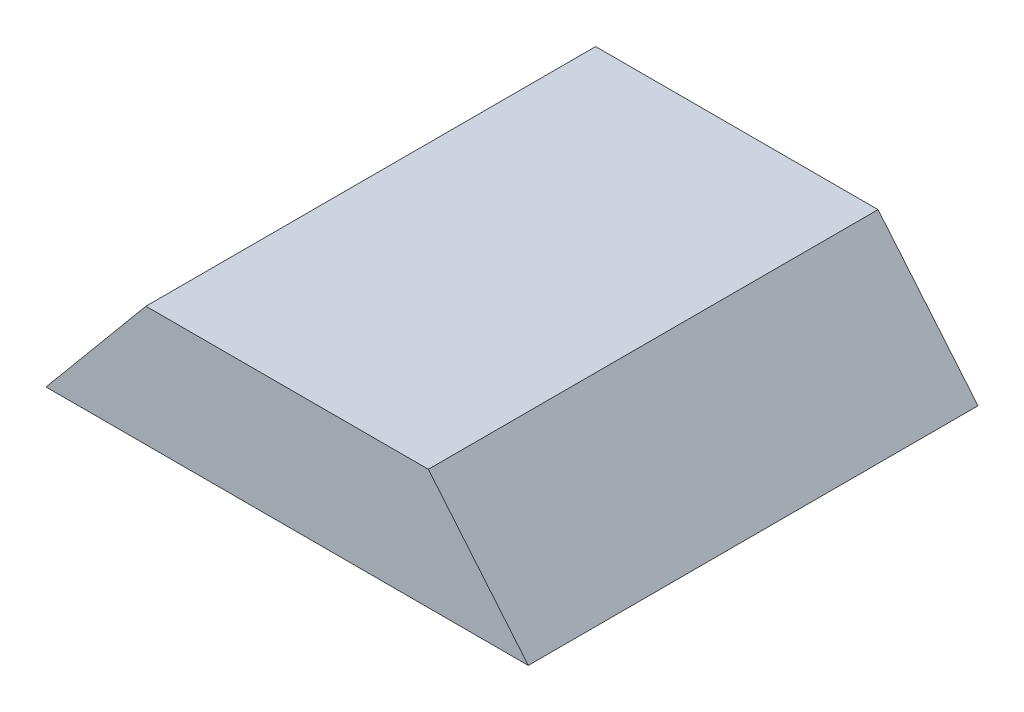
SolidWorks part; units mm, degrees
ref_plane "Alzado" through (0, 0, 0) normal (0, 0, 1) x (1, 0, 0)
ref_plane "Planta" through (0, 0, 0) normal (0, 1, 0) x (1, 0, 0)
ref_plane "Vista lateral" through (0, 0, 0) normal (1, 0, 0) x (0, 0, -1)
sketch "Croquis1" plane through (0, 0, 0) normal (0, 0, 1) x (1, 0, 0)
  line L0 (-55, 0) -> (-56.3017, 0)
  line L1 (-56.3017, 0) -> (-32.9684, 28)
  line L2 (-32.5, 27) -> (32.5, 27)
  line L3 (-32.5, 27) -> (-55, 0)
  line L4 (32.9684, 28) -> (-32.9684, 28)
  line L5 (0, 0) -> (0, 33.9502) construction
  line L6 (32.5, 27) -> (55, 0)
  line L7 (56.3017, 0) -> (32.9684, 28)
  line L8 (55, 0) -> (56.3017, 0)
  point P10 (0, 28)
  point P12 (0, 27)
  dimension "D1" = 1
  dimension "D2" = 32.5
  dimension "D3" = 55
  dimension "D4" = 1
  dimension "D5" = 27
extrude "Saliente-Extruir1" add sketch "Croquis1" along normal blind 104
sketch "Croquis4" plane through (0, 0, 104) normal (0, 0, 1) x (1, 0, 0)
  line L0 (-56.3017, 0) -> (56.3017, 0)
  line L1 (56.3017, 0) -> (32.9684, 28)
  line L2 (32.9684, 28) -> (-32.9684, 28)
  line L3 (-32.9684, 28) -> (-56.3017, 0)
extrude "Saliente-Extruir2" add sketch "Croquis4" along normal blind 1
